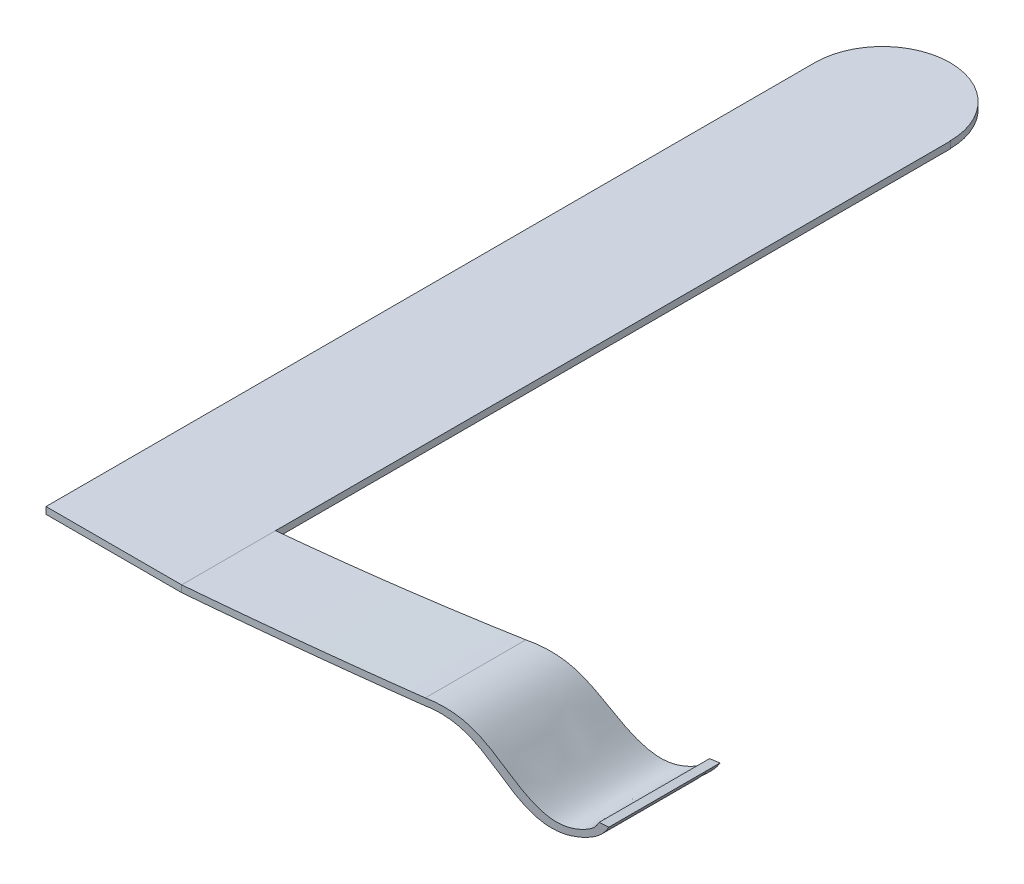
SolidWorks part; units mm, degrees
ref_plane "Спереди" through (0, 0, 0) normal (0, 0, 1) x (1, 0, 0)
ref_plane "Сверху" through (0, 0, 0) normal (0, 1, 0) x (1, 0, 0)
ref_plane "Справа" through (0, 0, 0) normal (1, 0, 0) x (0, 0, -1)
sketch "Эскиз1" plane through (0, 0, 0) normal (0, 0, 1) x (1, 0, 0)
  line L0 (0.0035, 30.6) -> (0, 28.1) construction
  line L1 (0.0035, 30.6) -> (-1.4965, 30.6)
  line L3 (26.5, 30.6) -> (-26.5, 30.6) construction
  line L4 (-1.4965, 30.6) -> (-1.4965, 30.45)
  line L5 (-1.4965, 30.45) -> (1.5035, 30.45)
  line L6 (1.5035, 30.45) -> (1.5035, 30.6)
  line L7 (0.8052, 30.6) -> (0.9654, 30.6) construction
  line L8 (1.5035, 30.6) -> (0.0035, 30.6)
  dimension "D1" = 3
  dimension "D2" = 0.15
extrude "Бобышка-Вытянуть1" add sketch "Эскиз1" along normal blind 17
sketch "Эскиз5" plane through (0, 28.11, 0) normal (0, 1, 0) x (1, 0, 0)
  line L0 (1.5035, -17) -> (1.5035, -14.9245)
  line L1 (1.5035, -17) -> (1.5035, 0) construction
  line L2 (0, 0) -> (0, -30.2127) construction
  line L3 (0, 0) -> (20.1116, -23.9681) construction
  line L4 (9.6418, -11.4907) -> (10.97, -13.0736)
  arc A0 (1.5035, -14.9245) -> (9.6418, -11.4907) centre (0, 0) ccw
  arc A1 (1.5035, -17) -> (10.97, -13.0736) centre (0, 0) ccw
  dimension "D1" = 40
extrude "Бобышка-Вытянуть2" add sketch "Эскиз5" along normal up to vertex (2.49 mm away)
sketch "Эскиз6" plane through (0, 0, 17) normal (0, 0, 1) x (1, 0, 0)
  line L0 (1.5035, 28.11) -> (10.97, 28.11) construction
  line L1 (1.5035, 30.6) -> (-1.4965, 30.6) construction
  line L3 (8.5219, 28.4543) -> (8.6576, 28.3904)
  line L4 (1.5035, 30.45) -> (1.5035, 27.8646)
  line L5 (1.5035, 27.8646) -> (11.1625, 27.8646)
  line L6 (11.1625, 27.8646) -> (11.137, 30.6)
  line L7 (11.137, 30.6) -> (1.5035, 30.6)
  spline S0 degree 2 poles (1.5035, 30.45) (3.7156, 30.45) (5.8791, 29.9939) knots 0 0 0 1 1 1
  spline S1 degree 3 poles (5.8791, 29.9939) (6.3078, 29.9381) (7.0186, 29.2805) (7.6902, 27.9182) (8.518, 28.1707) (8.6195, 28.3137) (8.6483, 28.3707) (8.6576, 28.3904) knots 0 0 0 0 0.289831 0.733668 0.815432 0.844658 0.859635 0.859635 0.859635 0.859635
  spline S2 degree 1 poles (1.5035, 30.6) (5.9044, 30.1418) knots 0 0 1 1 construction
  spline S3 degree 1 poles (5.9044, 30.1418) (8.5219, 28.4543) knots 0 0 1 1 construction
  spline S4 degree 3 poles (1.5035, 30.6) (2.9784, 30.6) (4.4612, 30.4457) (5.9044, 30.1418) knots 0 0 0 0 0.998713 0.998713 0.998713 0.998713
  spline S5 degree 3 poles (5.9044, 30.1418) (6.0701, 30.1196) (6.4032, 30.004) (6.8822, 29.5946) (7.349, 28.8424) (7.8014, 28.3351) (8.1099, 28.2527) (8.2906, 28.2578) (8.4263, 28.3149) (8.4766, 28.3685) (8.5093, 28.4274) (8.5219, 28.4543) knots 0.001207 0.001207 0.001207 0.001207 0.108511 0.215814 0.430421 0.645028 0.69868 0.752332 0.805984 0.832809 0.859635 0.859635 0.859635 0.859635
  dimension "D1" = 0.15
  dimension "D2" = 0.15
extrude "Вырез-Вытянуть1" cut sketch "Эскиз6" against normal blind 20
sketch "Эскиз7" plane through (0, 30.6, 0) normal (0, 1, 0) x (1, 0, 0)
  line L0 (1.4965, 0) -> (1.5035, 0)
  line L1 (-1.4965, 0) -> (1.4965, 0)
  arc A0 (1.4965, 0) -> (-1.4965, 0) centre (0, 0) ccw
extrude "Бобышка-Вытянуть3" add sketch "Эскиз7" against normal up to vertex contours A0 L1
